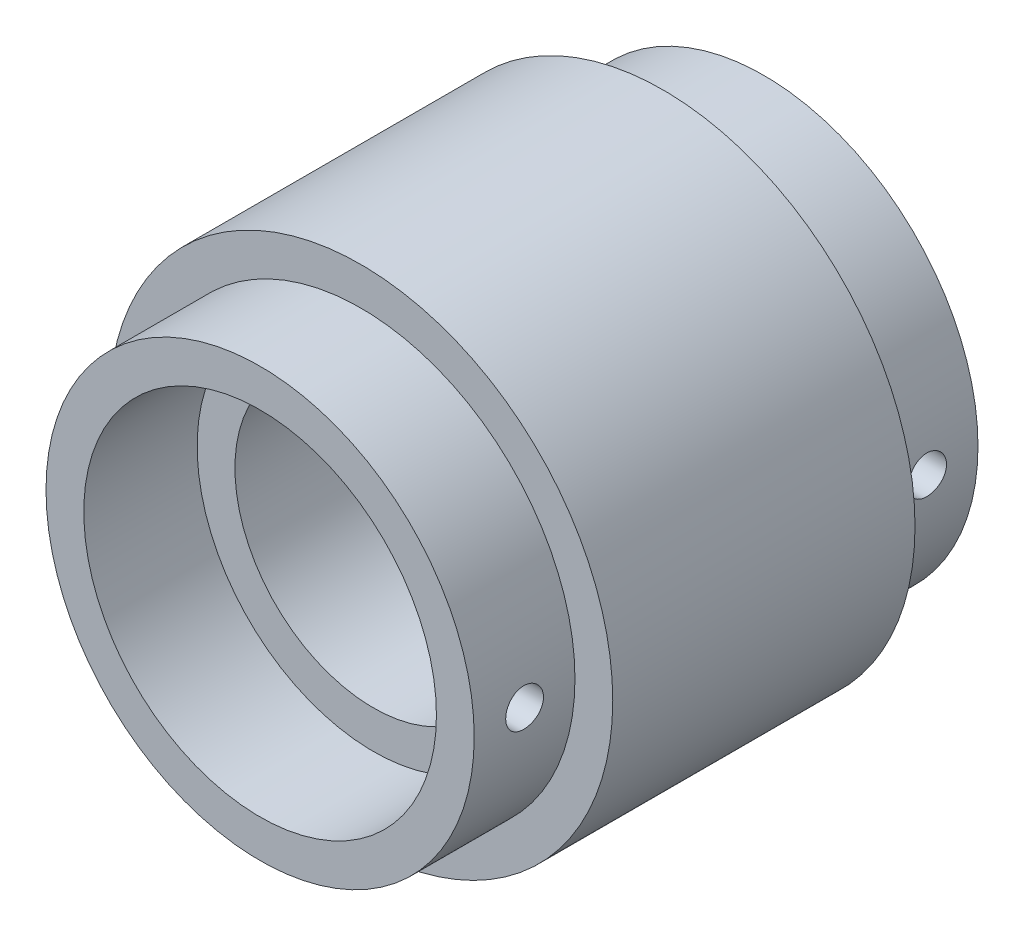
SolidWorks part; units mm, degrees
ref_plane "Płaszczyzna przednia" through (0, 0, 0) normal (0, 0, 1) x (1, 0, 0)
ref_plane "Płaszczyzna górna" through (0, 0, 0) normal (0, 1, 0) x (1, 0, 0)
ref_plane "Płaszczyzna prawa" through (0, 0, 0) normal (1, 0, 0) x (0, 0, -1)
sketch "Sketch1" plane through (0, 0, 0) normal (0, 0, 1) x (1, 0, 0)
  circle A0 centre (0, 0) radius 20
  dimension "D1" = 40
extrude "Boss-Extrude1" add sketch "Sketch1" along normal mid plane 40
hole_wizard "Hole1" positions "Sketch2" profile "Sketch3" legacy end condition through all
sketch "Sketch2" plane through (0, 0, 20) normal (0, 0, 1) x (1, 0, 0)
  point P0 (0, 0)
sketch "Sketch3" plane through (0, 0, 20) normal (1, 0, 0) x (0, -1, 0)
  line L0 (0, 0) -> (0, 46.6095)
  line L1 (0, 46.6095) -> (11, 40)
  line L2 (11, 40) -> (11, 9)
  line L3 (11, 9) -> (14, 9)
  line L4 (14, 0) -> (0, 0)
  line L5 (0, -11.3109) -> (0, 121.1557) construction
  line L6 (0, 46.6095) -> (-11, 40) construction
  line L7 (14, 9) -> (14, 0)
  dimension "Depth" = 40
  dimension "Drill Angle" = 118
  dimension "Diameter" = 22
  dimension "C-Bore Diameter" = 28
  dimension "C-Bore Depth" = 9
sketch "Sketch4" plane through (0, 0, 20) normal (0, 0, 1) x (1, 0, 0)
  circle A0 centre (0, 0) radius 20
  circle A1 centre (0, 0) radius 17
  circle A2 centre (0, 0) radius 20 construction
  dimension "D1" = 3
extrude "Cut-Extrude1" cut sketch "Sketch4" against normal blind 8
mirror "Mirror2" about plane through (0, 0, 0) normal (0, 0, 1) of "Cut-Extrude1", "Hole1"
sketch "Sketch5" plane through (0, 0, 0) normal (1, 0, 0) x (0, 0, -1)
  line L0 (-16, 0) -> (16, 0) construction
  line L3 (-20, 17) -> (-20, -17) construction
  circle A0 centre (-16, 0) radius 1.5
  circle A1 centre (16, 0) radius 1.5
  dimension "D2" = 3
  dimension "D3" = 3
  dimension "D1" = 4
extrude "Cut-Extrude2" cut sketch "Sketch5" along normal up to surface (17 mm away) up to face at (17, 0, -12)
